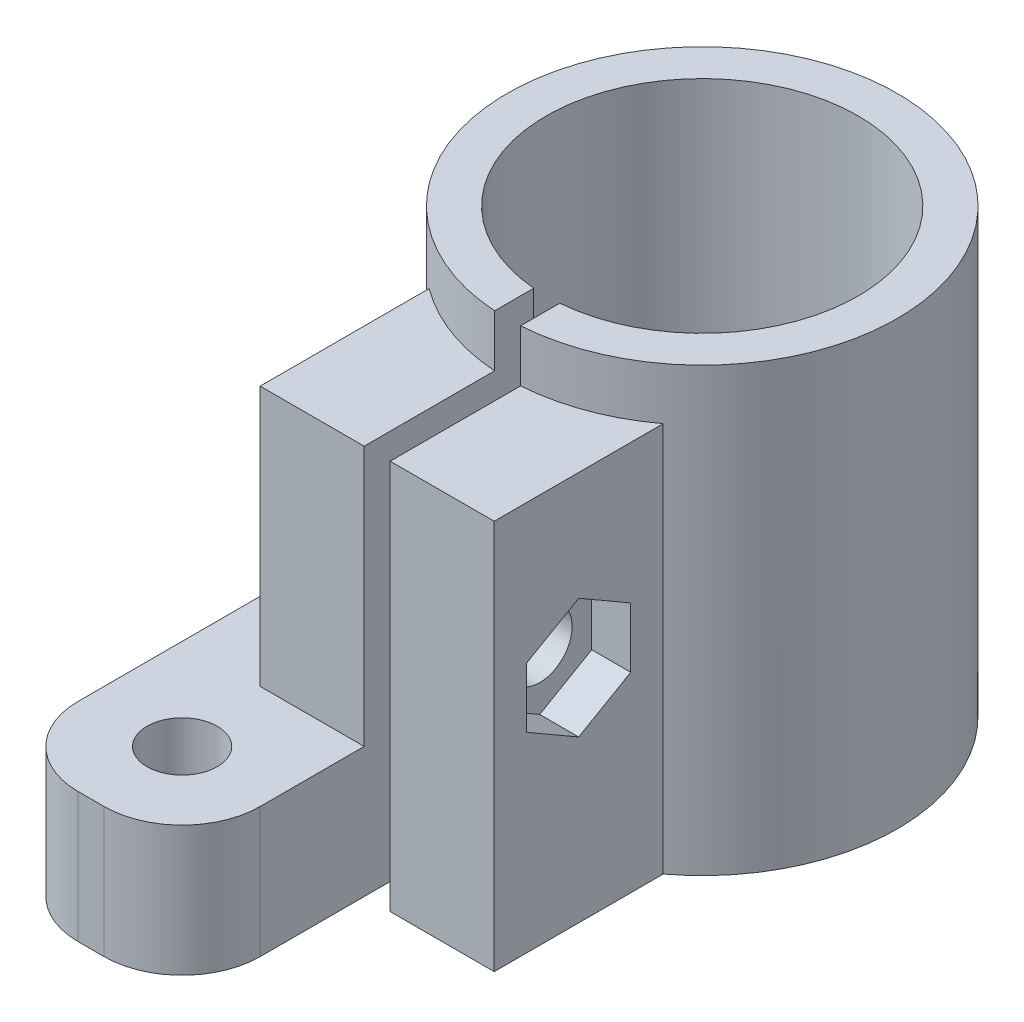
SolidWorks part; units mm, degrees
ref_plane "前视基准面" through (0, 0, 0) normal (0, 0, 1) x (1, 0, 0)
ref_plane "上视基准面" through (0, 0, 0) normal (0, 1, 0) x (1, 0, 0)
ref_plane "右视基准面" through (0, 0, 0) normal (1, 0, 0) x (0, 0, -1)
sketch "草图1" plane through (0, 0, 0) normal (0, 1, 0) x (1, 0, 0)
  circle A0 centre (0, 0) radius 6
  circle A1 centre (0, 0) radius 7.5
  dimension "D1" = 12
  dimension "D2" = 15
extrude "凸台-拉伸1" add sketch "草图1" along normal blind 17
ref_plane "基准面1" through (0, 0, 7.5) normal (0, 0, 1) x (1, 0, 0)
sketch "草图2" plane through (0, 0, 7.5) normal (0, 0, 1) x (1, 0, 0)
  line L0 (0, 0) -> (0, 17) construction
  line L1 (6, 17) -> (-6, 17) construction
  line L2 (-7.5, 0) -> (7.5, 0) construction
  line L3 (-0.5, 17) -> (0.5, 17)
  line L4 (-0.5, 17) -> (-0.5, 0)
  line L5 (-0.5, 0) -> (0.5, 0)
  line L6 (0.5, 17) -> (0.5, 0)
  line L7 (-0.5, 17) -> (0.5, 0) construction
  line L8 (-0.5, 0) -> (0.5, 17) construction
  point P5 (0, 8.5)
  dimension "D1" = 1
extrude "切除-拉伸1" cut sketch "草图2" against normal up to next
sketch "草图3" plane through (0, 0, 7.5) normal (0, 0, 1) x (1, 0, 0)
  line L0 (-7.5, 0) -> (7.5, 0) construction
  line L1 (-0.5, 17) -> (-4.5, 17)
  line L2 (-0.5, 17) -> (-0.5, 0)
  line L3 (-0.5, 0) -> (-4.5, 0)
  line L4 (-4.5, 17) -> (-4.5, 0)
  line L6 (0.5, 17) -> (4.5, 17)
  line L7 (0.5, 17) -> (0.5, 0)
  line L8 (0.5, 0) -> (4.5, 0)
  line L9 (4.5, 17) -> (4.5, 0)
  dimension "D1" = 4
extrude "凸台-拉伸2" add sketch "草图3" along normal blind 5 and the other way up to next
sketch "草图7" plane through (0, 17, 0) normal (0, 1, 0) x (1, 0, 0)
  line L0 (-4.5, -6) -> (-4.5, -12.5)
  line L1 (-4.5, -12.5) -> (4.5, -12.5)
  line L2 (4.5, -12.5) -> (4.5, -6)
  arc A0 (-4.5, -6) -> (4.5, -6) centre (0, 0) ccw
extrude "切除-拉伸4" cut sketch "草图7" against normal blind 2
sketch "草图4" plane through (-4.5, 0, 0) normal (-1, 0, 0) x (0, 0, 1)
  line L0 (6, 7.5) -> (12.5, 7.5) construction
  line L1 (6, 15) -> (6, 0) construction
  line L2 (12.5, 15) -> (12.5, 0) construction
  line L3 (9.25, 8.5) -> (9.25, 6.5) construction
  circle A0 centre (9.25, 8.5) radius 1.25
  circle A1 centre (9.25, 6.5) radius 1.25 construction
  point P9 (9.25, 7.5)
  dimension "D2" = 2.5
  dimension "D1" = 2
extrude "切除-拉伸2" cut sketch "草图4" against normal up to surface (9 mm away) up to face at (4.5, 7.5, 9.25)
sketch "草图5" plane through (4.5, 0, 0) normal (1, 0, 0) x (0, 0, -1)
  line L1 (-9.25, 6.1906) -> (-7.25, 7.3453)
  line L2 (-7.25, 7.3453) -> (-7.25, 9.6547)
  line L3 (-7.25, 9.6547) -> (-9.25, 10.8094)
  line L4 (-9.25, 10.8094) -> (-11.25, 9.6547)
  line L5 (-11.25, 9.6547) -> (-11.25, 7.3453)
  line L6 (-11.25, 7.3453) -> (-9.25, 6.1906)
  circle A0 centre (-9.25, 8.5) radius 2 construction
  dimension "D1" = 4
extrude "切除-拉伸3" cut sketch "草图5" against normal blind 1.5
sketch "草图8" plane through (0, 0, 0) normal (0, 1, 0) x (1, 0, 0)
  line L0 (-7.5, 0) -> (-7.5, -19.5)
  line L1 (-7.5, -19.5) -> (-0.5, -19.5)
  line L2 (-0.5, -19.5) -> (-0.5, -12.5)
  line L5 (-0.5, -12.5) -> (-4.5, -12.5)
  line L6 (-4.5, -12.5) -> (-4.5, -6)
  line L7 (-4.5, -6) -> (-7.5, 0)
  arc A0 (0.5, -7.4833) -> (-0.5, -7.4833) centre (0, 0) ccw construction
extrude "凸台-拉伸3" add sketch "草图8" along normal blind 5
sketch "草图9" plane through (0, 5, 0) normal (0, 1, 0) x (1, 0, 0)
  line L0 (-0.5, -16) -> (-7.5, -16) construction
  line L1 (-0.5, -19.5) -> (-0.5, -12.5) construction
  line L2 (-7.5, 0) -> (-7.5, -19.5) construction
  circle A1 centre (-4, -16) radius 1.35
  dimension "D1" = 2.7
extrude "切除-拉伸5" cut sketch "草图9" against normal up to next
fillet "圆角1" radius 3 2 edges at (-0.5, 2.5, 19.5) (-7.5, 2.5, 19.5)
